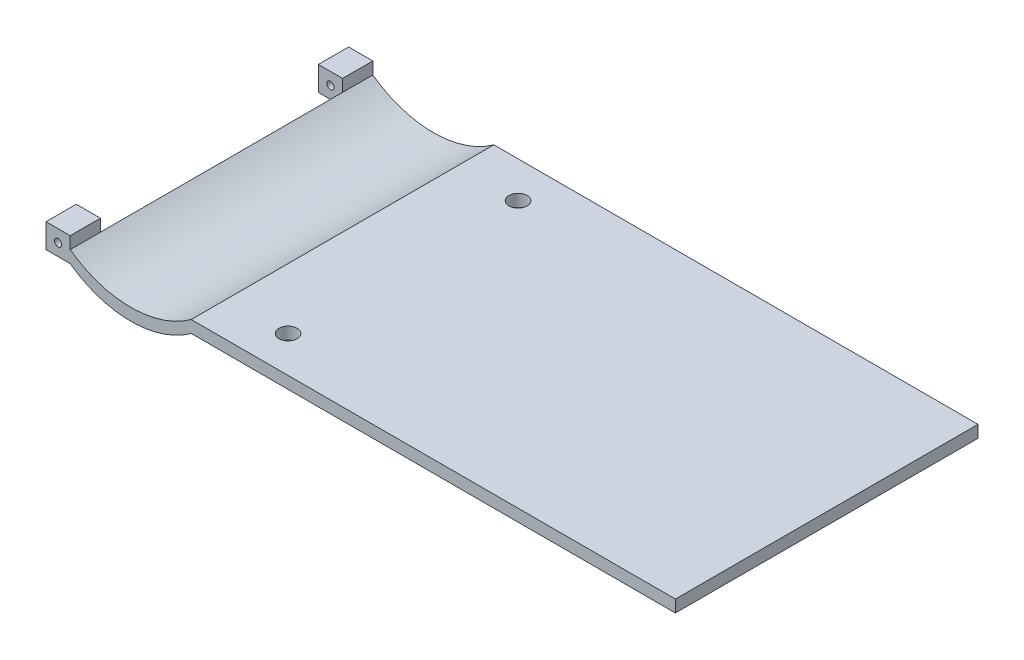
SolidWorks part; units mm, degrees
material "PBT 一般用途"
ref_plane "前视基准面" through (0, 0, 0) normal (0, 0, 1) x (1, 0, 0)
ref_plane "上视基准面" through (0, 0, 0) normal (0, 1, 0) x (1, 0, 0)
ref_plane "右视基准面" through (0, 0, 0) normal (1, 0, 0) x (0, 0, -1)
sketch "草图1" plane through (0, 0, 0) normal (0, 0, 1) x (1, 0, 0)
  line L1 (400, -10) -> (-400, -10)
  line L2 (400, -10) -> (400, 10)
  line L3 (400, 10) -> (-400, 10)
  line L4 (-400, -10) -> (-400, 10)
  line L5 (400, -10) -> (-400, 10) construction
  line L6 (400, 10) -> (-400, -10) construction
  line L7 (-600, -10) -> (-640, -10)
  line L8 (-600, -10) -> (-600, 30)
  line L9 (-600, 10) -> (-600, -10)
  line L10 (-600, 30) -> (-640, 30)
  line L11 (-640, -10) -> (-640, 30)
  arc A0 (-600, -10) -> (-400, -10) centre (-500, 127.4773) ccw
  arc A1 (-600, 10) -> (-400, 10) centre (-500, 147.4773) ccw
  circle A2 centre (-620, 10) radius 6
  point P0 (0, 0)
  dimension "D3" = 170
  dimension "D4" = 170
  dimension "D1" = 800
  dimension "D2" = 20
  dimension "D5" = 200
  dimension "D6" = 20
  dimension "D7" = 40
  dimension "D8" = 40
extrude "凸台-拉伸1" add sketch "草图1" along normal blind 500
sketch "草图5" plane through (0, 10, 0) normal (0, 1, 0) x (1, 0, 0)
  line L0 (-400, -250) -> (-286.9738, -250) construction
  line L3 (-400, -500) -> (-400, 0) construction
  line L4 (400, 0) -> (-400, 0) construction
  circle A0 centre (-300, -60) radius 15
  circle A1 centre (-300, -440) radius 15
  circle A2 centre (-300, -440) radius 15
  dimension "D1" = 100
  dimension "D3" = 30
  dimension "D2" = 60
extrude "切除-拉伸2" cut sketch "草图5" against normal through all contours A1 | A0
sketch "草图6" plane through (0, 30, 0) normal (0, 1, 0) x (1, 0, 0)
  line L0 (-600, -500) -> (-600, 0) construction
  line L1 (-600, -50) -> (-640, -50)
  line L2 (-600, -50) -> (-600, -450)
  line L3 (-600, -450) -> (-640, -450)
  line L4 (-640, -50) -> (-640, -450)
  line L5 (-640, -500) -> (-640, 0) construction
  line L6 (-600, 0) -> (-640, 0) construction
  dimension "D1" = 400
  dimension "D2" = 50
extrude "切除-拉伸3" cut sketch "草图6" against normal through all
